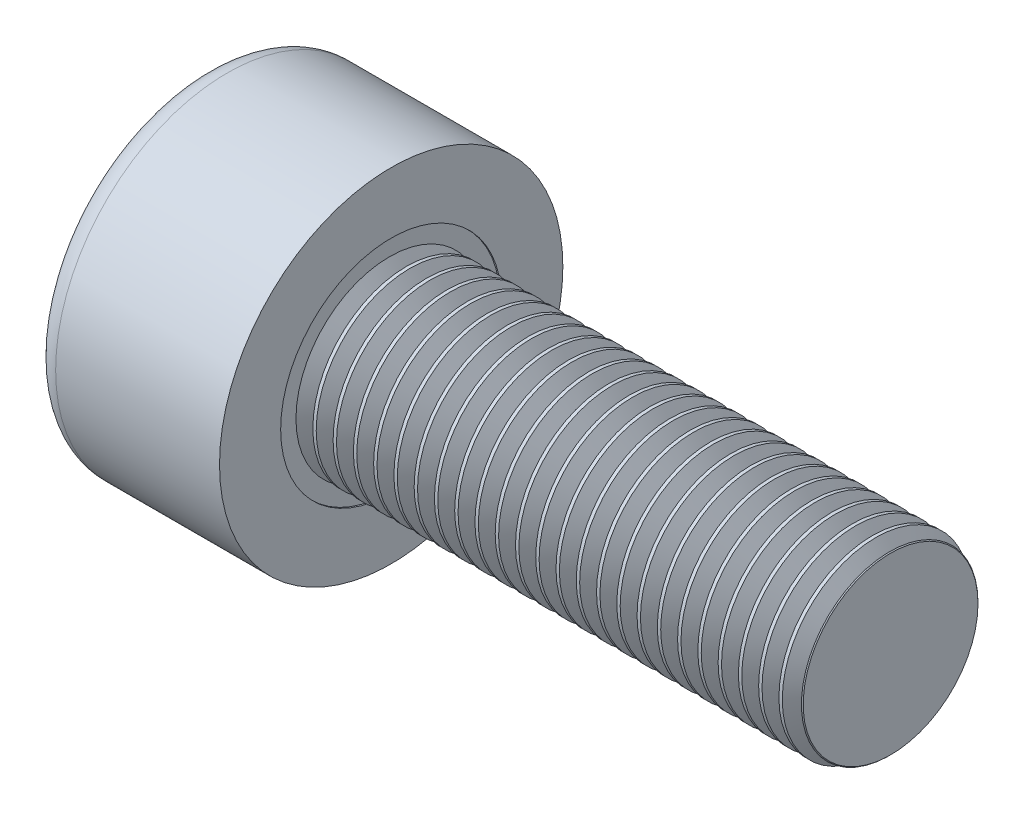
SolidWorks part; units mm, degrees
ref_plane "Front" through (0, 0, 0) normal (0, 0, 1) x (1, 0, 0)
ref_plane "Top" through (0, 0, 0) normal (0, 1, 0) x (1, 0, 0)
ref_plane "Right" through (0, 0, 0) normal (1, 0, 0) x (0, 0, -1)
sketch "Sketch1" plane through (0, 0, 0) normal (1, 0, 0) x (0, 0, -1)
  circle A0 centre (0, 0) radius 2.75
  dimension "dk" = 5.5
extrude "BaseHead" add sketch "Sketch1" along normal blind 3
sketch "Sketch2" plane through (3, 0, 0) normal (1, 0, 0) x (0, 0, -1)
  circle A0 centre (0, 0) radius 1.5
  dimension "d" = 3
extrude "BaseBody" add sketch "Sketch2" along normal blind 8
cosmetic thread "ThreadCosmetic1" [suppressed] parameters "b"=8, "D2"=2.459
sketch "Sketch3" plane through (0, 0, 0) normal (1, 0, 0) x (0, 0, -1)
  line L1 (1.4434, 0) -> (0.7217, 1.25)
  line L2 (0.7217, 1.25) -> (-0.7217, 1.25)
  line L3 (-0.7217, 1.25) -> (-1.4434, 0)
  line L4 (-1.4434, 0) -> (-0.7217, -1.25)
  line L5 (-0.7217, -1.25) -> (0.7217, -1.25)
  line L6 (0.7217, -1.25) -> (1.4434, 0)
  circle A0 centre (0, 0) radius 1.25 construction
  dimension "s" = 2.5
  dimension "e" = 2.8868
extrude "HexagonSocket" cut sketch "Sketch3" along normal blind 1.3
sketch "Sketch4" plane through (-4.1961, 0.75, 0) normal (0, 0, 1) x (-1, 0, 0)
  line L0 (-5.4961, 2) -> (-6.2178, 0.75)
  line L2 (-6.2178, 0.75) -> (-5.4961, 0.75)
  line L3 (-5.4961, 0.75) -> (-5.4961, 2)
  line L4 (-5.0351, 0.75) -> (0.839, 0.75) construction
  line L5 (-15.1961, 0.75) -> (-7.1961, 0.75) construction
  line L6 (-7.1961, 0.75) -> (-4.1961, 0.75) construction
  dimension "m" = 60
revolve "Cut-Revolve1" cut sketch "Sketch4" angle 360 about L4
fillet "HeadFillet" [suppressed] radius 0.1
fillet "TopFillet" radius 0.375 1 edges at (0, 0, -2.75)
chamfer "Chamfer1" distance 0.1 angle 45 1 edges at (11, 0, -1.5)
sketch "Sketch5" plane through (0, 0, 0) normal (0, 0, 1) x (1, 0, 0)
  line L0 (10.9, 1.2657) -> (11.0352, 1.5)
  line L1 (11.0352, 1.5) -> (11.0352, 1.7705)
  line L2 (11.0352, 1.7705) -> (10.7647, 1.7705)
  line L3 (10.7647, 1.7705) -> (10.7647, 1.5)
  line L4 (10.7647, 1.5) -> (10.9, 1.2657)
  line L5 (0, 0) -> (7.8886, 0) construction
  line L6 (10.9, -1.5) -> (10.9, 1.5) construction
  dimension "D1" = 3
  dimension "D2" = 0.2705
revolve "Cut-Revolve10" cut sketch "Sketch5" angle 360 about L5
pattern_linear "LPattern10" count 25 spacing 0.3246 along (-1, 0, 0) of "Cut-Revolve10"
equation "\"r1@TopFillet\" = \"d@Sketch2\" / 8"
equation "\"D1@Chamfer1\" = \"r@HeadFillet\""
equation "\"D1@Sketch5\" = \"d@Sketch2\""
equation "\"D2@Sketch5\" =  ( \"d@Sketch2\" - \"D2@ThreadCosmetic1\" )  / 2"
equation "\"D3@LPattern10\" = \"D2@Sketch5\" * 1.2"
equation "\"D1@LPattern10\" = \"b@ThreadCosmetic1\" / \"D3@LPattern10\""
